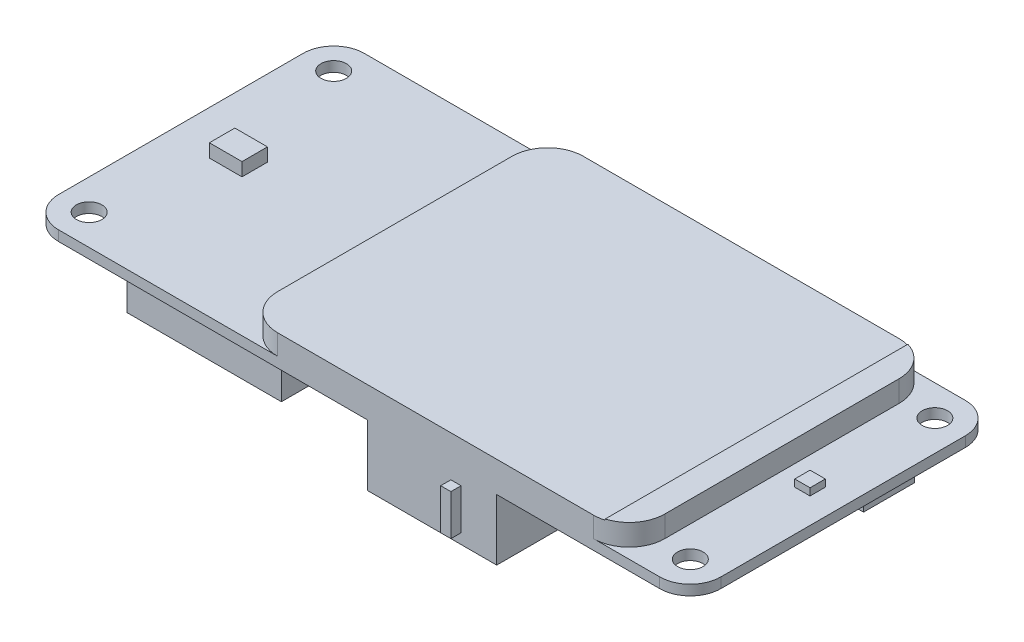
SolidWorks part; units mm, degrees
ref_plane "前视基准面" through (0, 0, 0) normal (0, 0, 1) x (1, 0, 0)
ref_plane "上视基准面" through (0, 0, 0) normal (0, 1, 0) x (1, 0, 0)
ref_plane "右视基准面" through (0, 0, 0) normal (1, 0, 0) x (0, 0, -1)
other "Configuration Table"
sketch "草图1" plane through (0, 0, 0) normal (0, 1, 0) x (1, 0, 0)
  line L1 (-29.5, 15) -> (29.5, 15)
  line L2 (-32.5, 12) -> (-32.5, -12)
  line L3 (-29.5, -15) -> (29.5, -15)
  line L4 (32.5, 12) -> (32.5, -12)
  line L5 (-32.5, 15) -> (32.5, -15) construction
  line L6 (-32.5, -15) -> (32.5, 15) construction
  arc A0 (29.5, -15) -> (32.5, -12) centre (29.5, -12) ccw
  arc A1 (29.5, 15) -> (32.5, 12) centre (29.5, 12) cw
  arc A2 (-32.5, -12) -> (-29.5, -15) centre (-29.5, -12) ccw
  arc A3 (-29.5, 15) -> (-32.5, 12) centre (-29.5, 12) ccw
  circle A4 centre (-29.5, 12) radius 1.25
  circle A5 centre (29.5, 12) radius 1.25
  circle A6 centre (-29.5, -12) radius 1.25
  circle A7 centre (29.5, -12) radius 1.25
  point P0 (0, 0)
  dimension "D3" = 3
  dimension "D4" = 2.5
  dimension "D1" = 65
  dimension "D2" = 30
extrude "board" add sketch "草图1" along normal blind 1
sketch "草图2" plane through (0, 1, 0) normal (0, 1, 0) x (1, 0, 0)
  line L0 (29.5, 15) -> (-29.5, 15) construction
  line L1 (-11.5, 15) -> (26.5, 15)
  line L2 (-11.5, 15) -> (-11.5, -15)
  line L3 (-11.5, -15) -> (26.5, -15)
  line L4 (26.5, 15) -> (26.5, -15)
  line L5 (-29.5, -15) -> (29.5, -15) construction
  line L6 (-32.5, 12) -> (-32.5, -12) construction
  line L7 (32.5, -12) -> (32.5, 12) construction
  dimension "D1" = 6
  dimension "D2" = 21
extrude "screen" add sketch "草图2" along normal blind 2
fillet "screen-radius" radius 3.5 4 edges at (-11.5, 2, -15) (26.5, 2, -15) (26.5, 2, 15) (-11.5, 2, 15)
sketch "草图3" plane through (0, 0, 0) normal (0, -1, 0) x (1, 0, 0)
  line L0 (32.5, 12) -> (32.5, -12) construction
  line L1 (-25.5, -9) -> (25.5, -9)
  line L2 (-25.5, -9) -> (-25.5, -14)
  line L3 (-25.5, -14) -> (25.5, -14)
  line L4 (25.5, -9) -> (25.5, -14)
  line L6 (29.5, -15) -> (-29.5, -15) construction
  dimension "D1" = 5
  dimension "D2" = 51
  dimension "D3" = 7
  dimension "D4" = 1
extrude "plug" add sketch "草图3" along normal blind 7.5
sketch "草图4" plane through (0, 0, 0) normal (0, -1, 0) x (1, 0, 0)
  line L1 (-25.09, 12.68) -> (-9.95, 12.68)
  line L2 (-25.09, 12.68) -> (-25.09, -7.32)
  line L3 (-25.09, -7.32) -> (-9.95, -7.32)
  line L4 (-9.95, 12.68) -> (-9.95, -7.32)
  line L5 (-32.5, -12) -> (-32.5, 12) construction
  line L6 (-29.5, 15) -> (29.5, 15) construction
  dimension "D1" = 15.14
  dimension "D2" = 20
  dimension "D3" = 7.41
  dimension "D4" = 2.32
extrude "speaker" add sketch "草图4" along normal blind 5
sketch "草图5" plane through (0, 0, 0) normal (0, -1, 0) x (1, 0, 0)
  line L1 (0.8, 15) -> (13.5, 15)
  line L2 (0.8, 15) -> (0.8, 9)
  line L3 (0.8, 9) -> (13.5, 9)
  line L4 (13.5, 15) -> (13.5, 9)
  line L5 (-29.5, 15) -> (29.5, 15) construction
  line L6 (32.5, 12) -> (32.5, -12) construction
  point P5 (0, 0)
  point P9 (0, 0)
  dimension "D1" = 12.7
  dimension "D2" = 6
  dimension "D4" = 19
extrude "button" add sketch "草图5" along normal blind 6
sketch "草图6" plane through (0, 0, 15) normal (0, 0, 1) x (1, 0, 0)
  line L1 (13.5, -6) -> (0.8, -6) construction
  line L2 (13.5, -6) -> (13.5, 0) construction
  line L3 (9, -1) -> (10, -1)
  line L4 (9, -1) -> (9, -5)
  line L5 (9, -5) -> (10, -5)
  line L6 (10, -1) -> (10, -5)
  line L7 (-29.5, 0) -> (0.8, 0) construction
  dimension "D1" = 3.5
  dimension "D2" = 1
  dimension "D3" = 1
  dimension "D4" = 1
extrude "button-tap" add sketch "草图6" along normal blind 1
sketch "草图7" plane through (0, 1, 0) normal (0, 1, 0) x (1, 0, 0)
  line L1 (28.5, 0.75) -> (30, 0.75)
  line L2 (28.5, 0.75) -> (28.5, -0.75)
  line L3 (28.5, -0.75) -> (30, -0.75)
  line L4 (30, 0.75) -> (30, -0.75)
  line L6 (32.5, -12) -> (32.5, 12) construction
  point P4 (32.5, 0)
  point P5 (30, 0)
  dimension "D1" = 1.5
  dimension "D2" = 1.5
  dimension "D4" = 2.5
extrude "rgb-led" add sketch "草图7" along normal blind 0.7
sketch "草图8" plane through (0, 1, 0) normal (0, 1, 0) x (1, 0, 0)
  line L0 (29.5, 15) -> (23, 15) construction
  line L1 (-25, 1) -> (-28.2, 1)
  line L2 (-25, 1) -> (-25, -1.5)
  line L3 (-25, -1.5) -> (-28.2, -1.5)
  line L4 (-28.2, 1) -> (-28.2, -1.5)
  line L6 (-32.5, 12) -> (-32.5, -12) construction
  dimension "D1" = 3.2
  dimension "D2" = 2.5
  dimension "D3" = 14
  dimension "D4" = 4.3
extrude "mic" add sketch "草图8" along normal blind 1.3
sketch "草图9" plane through (0, 3, 0) normal (0, 1, 0) x (1, 0, 0)
  line L0 (26.5, -11.5) -> (26.5, 11.5) construction
  line L1 (26.5, -11.5) -> (26.5, 11.5)
  line L2 (24, 14.8541) -> (24, -14.8541)
  line L3 (32.5, -12) -> (32.5, 12) construction
  arc A0 (23, -15) -> (26.5, -11.5) centre (23, -11.5) ccw construction
  arc A1 (26.5, 11.5) -> (23, 15) centre (23, 11.5) ccw construction
  arc A2 (26.5, -11.5) -> (24, -14.8541) centre (23, -11.5) cw
  arc A3 (26.5, 11.5) -> (24, 14.8541) centre (23, 11.5) ccw
  dimension "D1" = 8.5
extrude "凸台-拉伸1" add sketch "草图9" along normal blind 0.1
